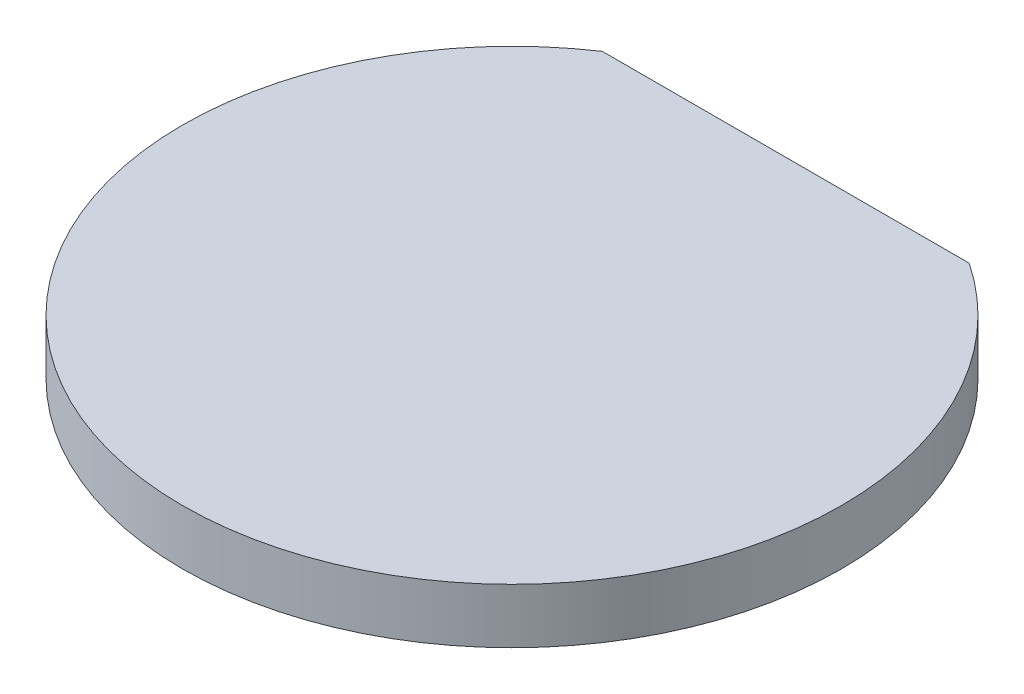
SolidWorks part; units mm, degrees
ref_plane "Front Plane" through (0, 0, 0) normal (0, 0, 1) x (1, 0, 0)
ref_plane "Top Plane" through (0, 0, 0) normal (0, 1, 0) x (1, 0, 0)
ref_plane "Right Plane" through (0, 0, 0) normal (1, 0, 0) x (0, 0, -1)
sketch "Sketch1" plane through (0, 0, 0) normal (0, 1, 0) x (1, 0, 0)
  circle A0 centre (0, 0) radius 38.1
  dimension "D1" = 76.2
extrude "Boss-Extrude1" add sketch "Sketch1" along normal blind 6.35
sketch "Sketch2" plane through (0, 6.35, 0) normal (0, 1, 0) x (1, 0, 0)
  line L0 (-21.209, 31.651) -> (21.209, 31.651)
  circle A0 centre (0, 0) radius 38.1 construction
  arc A1 (21.209, 31.651) -> (-21.209, 31.651) centre (0, 0) ccw
  dimension "D1" = 42.418
extrude "Cut-Extrude1" cut sketch "Sketch2" against normal through all both and the other way through all
